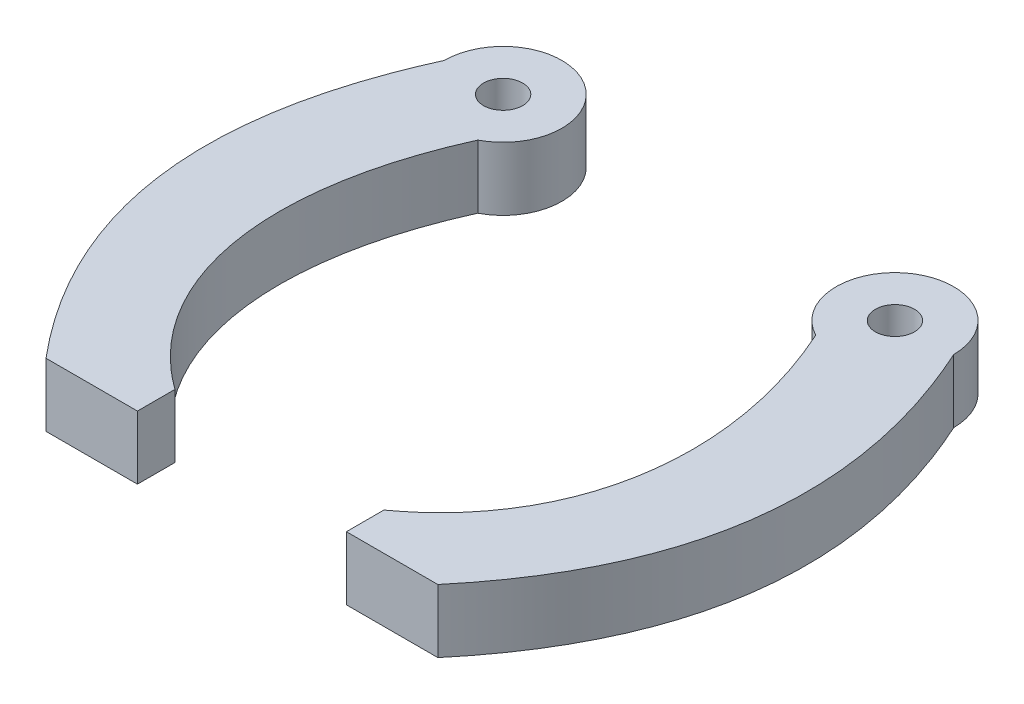
SolidWorks part; units mm, degrees
ref_plane "Front Plane" through (0, 0, 0) normal (0, 0, 1) x (1, 0, 0)
ref_plane "Top Plane" through (0, 0, 0) normal (0, 1, 0) x (1, 0, 0)
ref_plane "Right Plane" through (0, 0, 0) normal (1, 0, 0) x (0, 0, -1)
sketch "Sketch1" plane through (0, 0, 0) normal (0, 1, 0) x (1, 0, 0)
  line L0 (0, 0) -> (-30, 0) construction
  line L1 (0, 0) -> (0, -106.5873) construction
  line L2 (-5, 0) -> (-5, -70) construction
  line L3 (-5, -70) -> (-30, -70)
  line L4 (-5, -40) -> (-45, -40) construction
  line L5 (-16, -70) -> (-16, -64.2544)
  line L6 (5, -40) -> (45, -40) construction
  line L7 (5, 0) -> (5, -70) construction
  line L8 (16, -70) -> (16, -64.2544)
  line L9 (5, -70) -> (30, -70)
  circle A0 centre (-30, 0) radius 3
  circle A1 centre (-30, 0) radius 9
  circle A2 centre (30, 0) radius 9
  circle A3 centre (30, 0) radius 3
  spline S0 degree 2 poles (-30, -70) (-56.5321, -38.4963) (-39, 0) knots 0 0 0 1 1 1
  spline S1 degree 3 poles (-25.8769, -8) (-38.1383, -35.1788) (-30.511, -60.7073) (-5, -70) knots 0.085368 0.085368 0.085368 0.085368 1 1 1 1
  spline S2 degree 3 poles (25.8769, -8) (38.1383, -35.1788) (30.511, -60.7073) (5, -70) knots 0.085368 0.085368 0.085368 0.085368 1 1 1 1
  spline S3 degree 2 poles (30, -70) (56.5321, -38.4963) (39, 0) knots 0 0 0 1 1 1
  dimension "D2" = 6
  dimension "D3" = 18
  dimension "D1" = 30
  dimension "D4" = 70
  dimension "D5" = 25
  dimension "D6" = 25
  dimension "D7" = 40
  dimension "D8" = 40
  dimension "D9" = 14
  dimension "D10" = 8
  dimension "D11" = 14
extrude "JAW" add sketch "Sketch1" along normal blind 9.7 contours S1 A1 S0 L3 L5 | A1 A0 | L9 S3 A2 S2 L8 | A2 A3
other "Save Bodies1"
